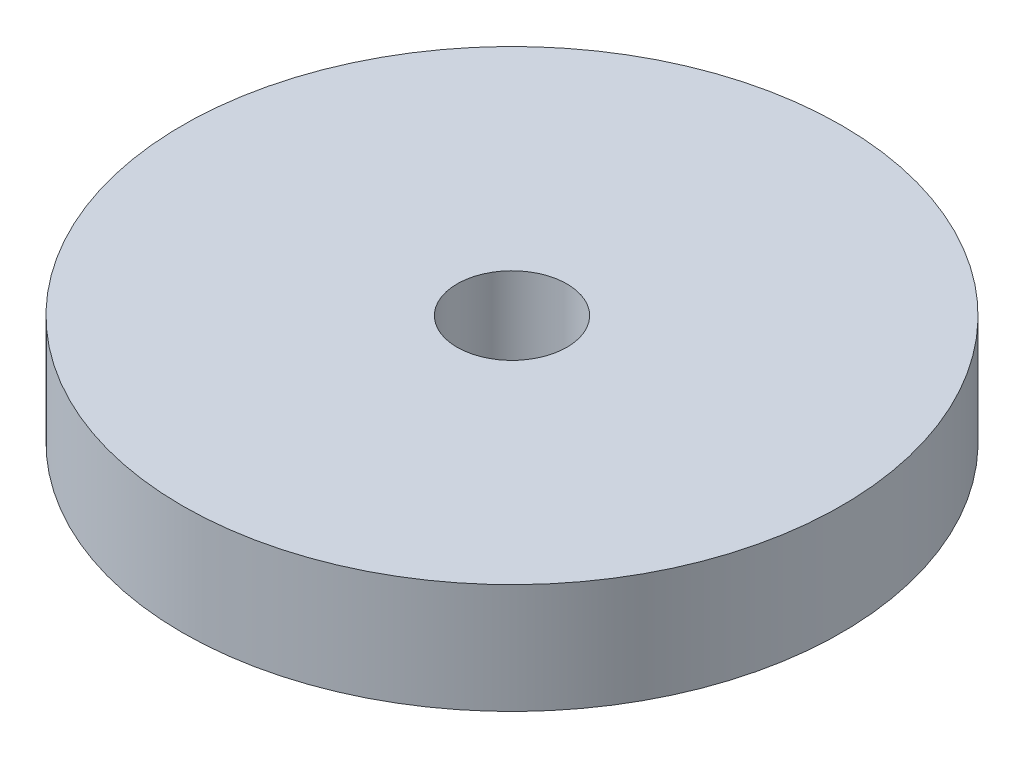
SolidWorks part; units mm, degrees
ref_plane "Front Plane" through (0, 0, 0) normal (0, 0, 1) x (1, 0, 0)
ref_plane "Top Plane" through (0, 0, 0) normal (0, 1, 0) x (1, 0, 0)
ref_plane "Right Plane" through (0, 0, 0) normal (1, 0, 0) x (0, 0, -1)
sketch "Sketch1" plane through (0, 0, 0) normal (0, 1, 0) x (1, 0, 0)
  circle A0 centre (0, 0) radius 15
  circle A1 centre (0, 0) radius 2.5
  dimension "D1" = 30
  dimension "D2" = 5
extrude "Boss-Extrude1" add sketch "Sketch1" along normal blind 5
